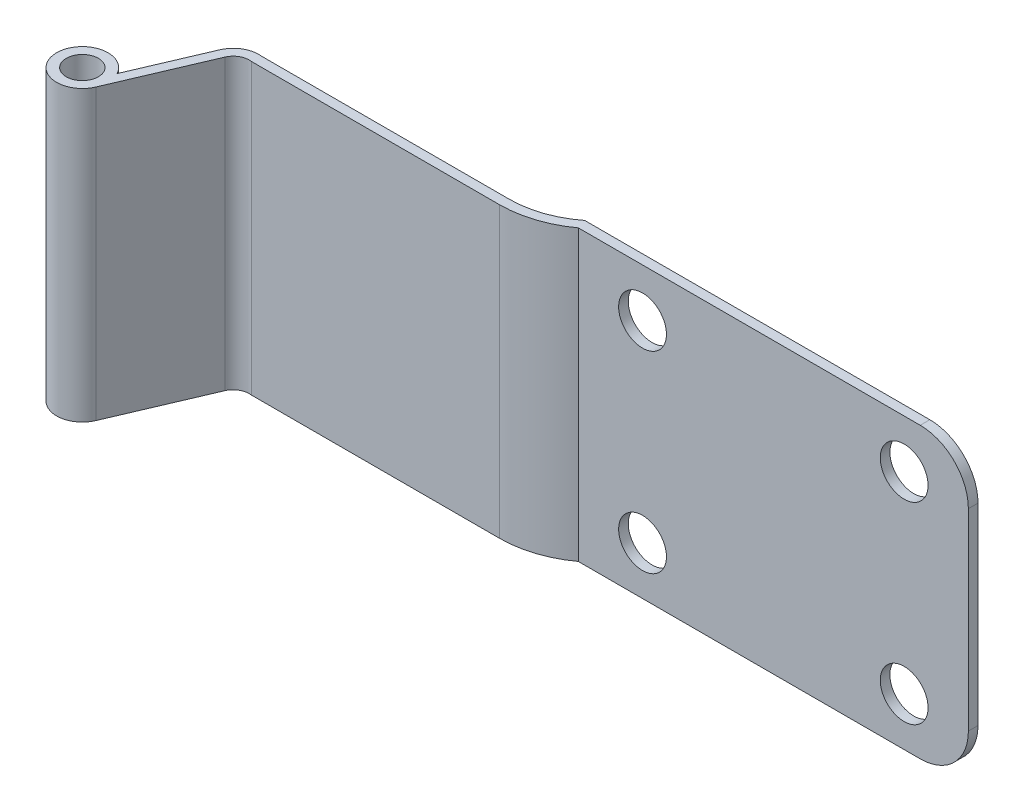
SolidWorks part; units mm, degrees
ref_plane "Front Plane" through (0, 0, 0) normal (0, 0, 1) x (1, 0, 0)
ref_plane "Top Plane" through (0, 0, 0) normal (0, 1, 0) x (1, 0, 0)
ref_plane "Right Plane" through (0, 0, 0) normal (1, 0, 0) x (0, 0, -1)
sketch "Sketch7" plane through (0, 0, 0) normal (0, 1, 0) x (1, 0, 0)
  line L0 (7.3579, -3.1403) -> (19.376, 25.0189)
  line L1 (24.6799, 27.9746) -> (102, 27.9746)
  line L2 (120.5032, 34) -> (242, 34)
  line L3 (7.0501, 3.7811) -> (16.6167, 26.1965)
  line L4 (24.8794, 30.9746) -> (102, 30.9746)
  line L5 (119.4991, 37) -> (242, 37)
  line L6 (242, 37) -> (242, 34)
  line L7 (4.5987, -1.9627) -> (16.6167, 26.1965) construction
  circle A0 centre (0, 0) radius 5
  arc A1 (7.0501, 3.7811) -> (7.3579, -3.1403) centre (0, 0) ccw
  arc A2 (19.376, 25.0189) -> (24.6799, 27.9746) centre (23.9361, 23.0727) cw
  arc A3 (102, 27.9746) -> (120.5032, 34) centre (102, 59.3981) ccw
  arc A4 (16.6167, 26.1965) -> (24.8794, 30.9746) centre (23.9361, 23.0727) cw
  arc A5 (102, 30.9746) -> (119.4991, 37) centre (102, 59.3981) ccw
  circle A6 centre (0, 0) radius 8 construction
  dimension "D1" = 10
  dimension "D3" = 42
  dimension "D4" = 3
  dimension "D5" = 110
  dimension "D2" = 3
extrude "Boss-Extrude1" add sketch "Sketch7" along normal blind 90
sketch "Sketch8" plane through (0, 0, -34) normal (0, 0, 1) x (1, 0, 0)
  line L0 (120.5032, 90) -> (242, 90) construction
  line L1 (120.5032, 0) -> (242, 0) construction
  line L2 (120.5032, 90) -> (120.5032, 0) construction
  line L3 (242, 90) -> (242, 0) construction
  circle A0 centre (140.5032, 75) radius 7.4474
  circle A1 centre (140.5032, 15) radius 7.4474
  circle A2 centre (222, 75) radius 7.4474
  circle A3 centre (222, 15) radius 7.4474
  point P8 (0, 0)
  point P9 (0, 0)
  point P10 (0, 0)
  point P15 (0, 0)
  point P20 (0, 0)
  dimension "D1" = 15
  dimension "D2" = 15
  dimension "D5" = 14.8948
  dimension "D3" = 20
  dimension "D4" = 20
extrude "Cut-Extrude1" cut sketch "Sketch8" against normal blind 90
fillet "Fillet1" radius 15 2 edges at (242, 0, -35.5) (242, 90, -35.5)
